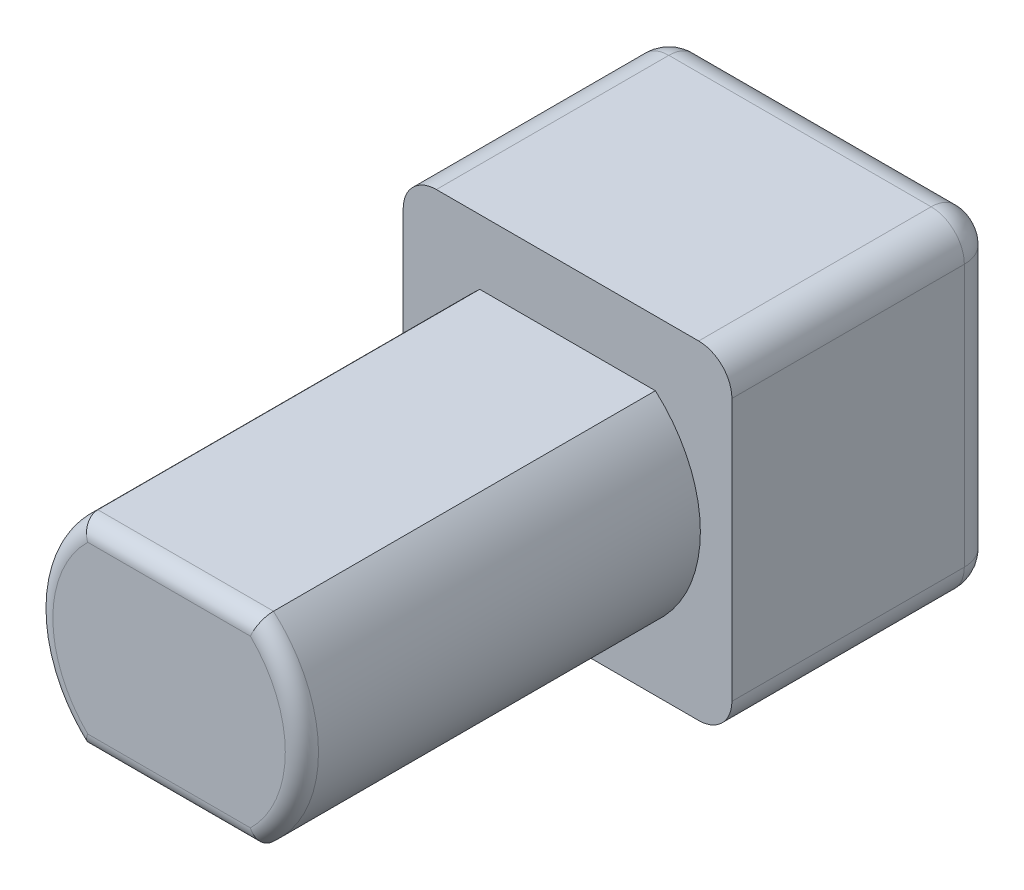
SolidWorks part; units mm, degrees
material "ABS"
ref_plane "Plan de face" through (0, 0, 0) normal (0, 0, 1) x (1, 0, 0)
ref_plane "Plan de dessus" through (0, 0, 0) normal (0, 1, 0) x (1, 0, 0)
ref_plane "Plan de droite" through (0, 0, 0) normal (1, 0, 0) x (0, 0, -1)
sketch "Esquisse1" plane through (0, 0, 0) normal (0, 0, 1) x (1, 0, 0)
  line L0 (-2.4749, 2.4749) -> (2.4749, -2.4749) construction
  line L1 (-2.4749, 2.4749) -> (2.4749, 2.4749)
  line L2 (-2.4749, 2.4749) -> (-2.4749, -2.4749)
  line L3 (-2.4749, -2.4749) -> (2.4749, -2.4749)
  line L4 (2.4749, 2.4749) -> (2.4749, -2.4749)
  line L5 (2.4749, 2.4749) -> (-2.4749, -2.4749) construction
  circle A0 centre (0, 0) radius 3.5 construction
  point P7 (0, 0)
  dimension "D1" = 7
extrude "Extrusion1" add sketch "Esquisse1" against normal blind 4
sketch "Esquisse3" plane through (0, 0, 0) normal (0, 0, 1) x (1, 0, 0)
  line L0 (-1.3229, 1.5) -> (1.3229, -1.5) construction
  line L1 (-1.3229, 1.5) -> (1.3229, 1.5)
  line L2 (-1.3229, 1.5) -> (-1.3229, -1.5) construction
  line L3 (-1.3229, -1.5) -> (1.3229, -1.5)
  line L4 (1.3229, 1.5) -> (1.3229, -1.5) construction
  arc A0 (-1.3229, 1.5) -> (-1.3229, -1.5) centre (0, 0) ccw
  arc A1 (1.3229, -1.5) -> (1.3229, 1.5) centre (0, 0) ccw
  dimension "D1" = 4
  dimension "D2" = 3
extrude "Extrusion5" add sketch "Esquisse3" along normal blind 6
fillet "Congé1" radius 0.5 8 edges at (2.4749, -2.4749, -2) (2.4749, 2.4749, -2) (0, 2.4749, -4) (2.4749, 0, -4) (0, -2.4749, -4) (-2.4749, -2.4749, -2) (-2.4749, 0, -4) (-2.4749, 2.4749, -2)
fillet "Congé2" radius 0.25 4 edges at (-2, 0, 6) (0, 1.5, 6) (2, 0, 6) (0, -1.5, 6)
